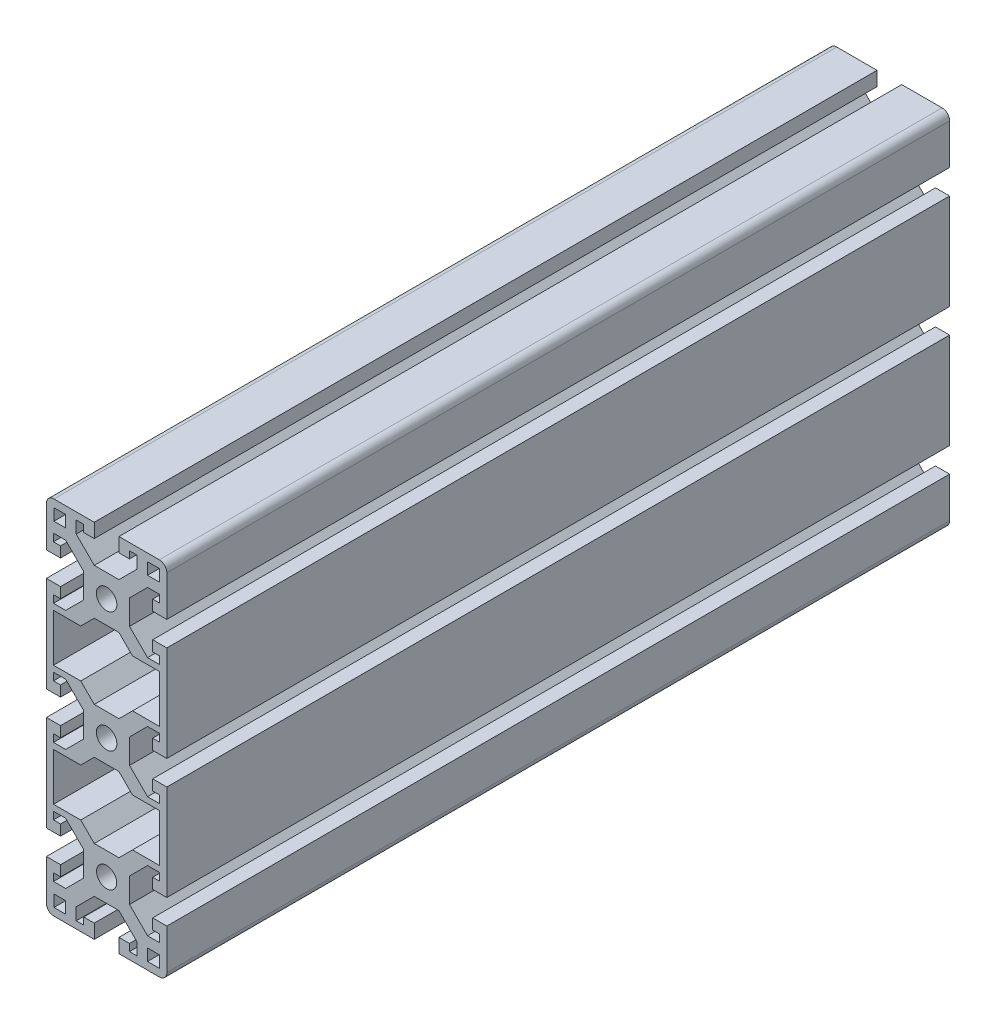
SolidWorks part; units mm, degrees
material "6063-T6"
ref_plane "Front Plane" through (0, 0, 0) normal (0, 0, 1) x (1, 0, 0)
ref_plane "Top Plane" through (0, 0, 0) normal (0, 1, 0) x (1, 0, 0)
ref_plane "Right Plane" through (0, 0, 0) normal (1, 0, 0) x (0, 0, -1)
sketch "Sketch1" plane through (0, 0, 0) normal (0, 1, 0) x (1, 0, 0)
  line L0 (0, -130) -> (0, 130)
  dimension "D1" = 260
other "40 series TS40-120LM(1)"
ref_plane "Plane1" through (0, 0, 130) normal (0, 0, -1) x (-1, 0, 0)
sketch "Sketch22" plane through (0, 0, 130) normal (0, 0, -1) x (-1, 0, 0)
  line L0 (15.3, -35.9) -> (20, -35.9)
  line L1 (3.35, 0) -> (7.6, 0) construction
  line L2 (7.6, 4.1) -> (7.6, -4.1)
  line L3 (7.6, -4.1) -> (13.6, -10.1)
  line L4 (13.6, -10.1) -> (17.65, -10.1)
  line L5 (17.65, -10.1) -> (17.65, -7.6)
  line L6 (17.65, -7.6) -> (15.3, -7.6)
  line L7 (15.3, -7.6) -> (15.3, -4.1)
  line L8 (15.3, -4.1) -> (20, -4.1)
  line L9 (20, -4.1) -> (20, -35.9)
  line L10 (0, -3.35) -> (0, -7.6) construction
  line L11 (-4.1, -7.6) -> (4.1, -7.6)
  line L12 (4.1, -7.6) -> (8.6, -12.1)
  line L13 (8.6, -12.1) -> (17.65, -12.1)
  line L14 (17.65, -12.1) -> (17.65, -27.9)
  line L15 (20, -20) -> (0, 0) construction
  line L16 (17.65, -20) -> (20, -20) construction
  line L17 (15.3, -32.4) -> (15.3, -35.9)
  line L18 (17.65, -32.4) -> (15.3, -32.4)
  line L19 (17.65, -29.9) -> (17.65, -32.4)
  line L20 (13.6, -29.9) -> (17.65, -29.9)
  line L21 (8.6, -27.9) -> (17.65, -27.9)
  line L22 (7.6, -35.9) -> (13.6, -29.9)
  line L23 (7.6, -44.1) -> (7.6, -35.9)
  line L24 (4.1, -32.4) -> (8.6, -27.9)
  line L25 (-4.1, -32.4) -> (4.1, -32.4)
  line L26 (3.35, -40) -> (7.6, -40) construction
  line L27 (15.3, -44.1) -> (20, -44.1)
  line L28 (15.3, -47.6) -> (15.3, -44.1)
  line L29 (17.65, -47.6) -> (15.3, -47.6)
  line L30 (17.65, -50.1) -> (17.65, -47.6)
  line L31 (13.6, -50.1) -> (17.65, -50.1)
  line L32 (7.6, -44.1) -> (13.6, -50.1)
  line L33 (0, -40) -> (19.2678, -59.2678) construction
  line L34 (20, -57.5) -> (20, -44.1)
  line L35 (17.5, -60) -> (4.1, -60)
  line L36 (4.1, -55.3) -> (4.1, -60)
  line L37 (7.6, -55.3) -> (4.1, -55.3)
  line L38 (7.6, -57.65) -> (7.6, -55.3)
  line L39 (10.1, -57.65) -> (7.6, -57.65)
  line L40 (10.1, -53.6) -> (10.1, -57.65)
  line L41 (4.1, -47.6) -> (10.1, -53.6)
  line L42 (4.1, -47.6) -> (-4.1, -47.6)
  line L43 (0, -40) -> (-19.2678, -59.2678) construction
  line L44 (-3.35, -40) -> (-7.6, -40) construction
  line L45 (-17.65, -20) -> (-20, -20) construction
  line L46 (-20, -20) -> (0, 0) construction
  line L47 (-3.35, 0) -> (-7.6, 0) construction
  line L48 (-4.1, -47.6) -> (-10.1, -53.6)
  line L49 (-10.1, -53.6) -> (-10.1, -57.65)
  line L50 (-10.1, -57.65) -> (-7.6, -57.65)
  line L51 (-7.6, -57.65) -> (-7.6, -55.3)
  line L52 (-7.6, -55.3) -> (-4.1, -55.3)
  line L53 (-4.1, -55.3) -> (-4.1, -60)
  line L54 (-17.5, -60) -> (-4.1, -60)
  line L55 (-20, -57.5) -> (-20, -44.1)
  line L56 (-7.6, -44.1) -> (-13.6, -50.1)
  line L57 (-13.6, -50.1) -> (-17.65, -50.1)
  line L58 (-17.65, -50.1) -> (-17.65, -47.6)
  line L59 (-17.65, -47.6) -> (-15.3, -47.6)
  line L60 (-15.3, -47.6) -> (-15.3, -44.1)
  line L61 (-15.3, -44.1) -> (-20, -44.1)
  line L62 (-4.1, -32.4) -> (-8.6, -27.9)
  line L63 (-7.6, -44.1) -> (-7.6, -35.9)
  line L64 (-7.6, -35.9) -> (-13.6, -29.9)
  line L65 (-8.6, -27.9) -> (-17.65, -27.9)
  line L66 (-13.6, -29.9) -> (-17.65, -29.9)
  line L67 (-17.65, -29.9) -> (-17.65, -32.4)
  line L68 (-17.65, -32.4) -> (-15.3, -32.4)
  line L69 (-15.3, -32.4) -> (-15.3, -35.9)
  line L70 (-17.65, -12.1) -> (-17.65, -27.9)
  line L71 (-8.6, -12.1) -> (-17.65, -12.1)
  line L72 (-4.1, -7.6) -> (-8.6, -12.1)
  line L73 (-20, -4.1) -> (-20, -35.9)
  line L74 (-15.3, -4.1) -> (-20, -4.1)
  line L75 (-15.3, -7.6) -> (-15.3, -4.1)
  line L76 (-17.65, -7.6) -> (-15.3, -7.6)
  line L77 (-17.65, -10.1) -> (-17.65, -7.6)
  line L78 (-13.6, -10.1) -> (-17.65, -10.1)
  line L79 (-7.6, -4.1) -> (-13.6, -10.1)
  line L80 (-7.6, 4.1) -> (-7.6, -4.1)
  line L81 (-15.3, -35.9) -> (-20, -35.9)
  line L82 (-20, 20) -> (0, 0) construction
  line L83 (-17.65, 20) -> (-20, 20) construction
  line L84 (-3.35, 40) -> (-7.6, 40) construction
  line L85 (0, 40) -> (-19.2678, 59.2678) construction
  line L86 (0, 40) -> (19.2678, 59.2678) construction
  line L87 (3.35, 40) -> (7.6, 40) construction
  line L88 (17.65, 20) -> (20, 20) construction
  line L89 (20, 20) -> (0, 0) construction
  line L90 (0, 3.35) -> (0, 7.6) construction
  line L91 (-15.3, 35.9) -> (-20, 35.9)
  line L92 (-7.6, 4.1) -> (-13.6, 10.1)
  line L93 (-13.6, 10.1) -> (-17.65, 10.1)
  line L94 (-17.65, 10.1) -> (-17.65, 7.6)
  line L95 (-17.65, 7.6) -> (-15.3, 7.6)
  line L96 (-15.3, 7.6) -> (-15.3, 4.1)
  line L97 (-15.3, 4.1) -> (-20, 4.1)
  line L98 (-20, 4.1) -> (-20, 35.9)
  line L99 (-4.1, 7.6) -> (-8.6, 12.1)
  line L100 (-8.6, 12.1) -> (-17.65, 12.1)
  line L101 (-17.65, 12.1) -> (-17.65, 27.9)
  line L102 (-15.3, 32.4) -> (-15.3, 35.9)
  line L103 (-17.65, 32.4) -> (-15.3, 32.4)
  line L104 (-17.65, 29.9) -> (-17.65, 32.4)
  line L105 (-13.6, 29.9) -> (-17.65, 29.9)
  line L106 (-8.6, 27.9) -> (-17.65, 27.9)
  line L107 (-7.6, 35.9) -> (-13.6, 29.9)
  line L108 (-7.6, 44.1) -> (-7.6, 35.9)
  line L109 (-4.1, 32.4) -> (-8.6, 27.9)
  line L110 (-15.3, 44.1) -> (-20, 44.1)
  line L111 (-15.3, 47.6) -> (-15.3, 44.1)
  line L112 (-17.65, 47.6) -> (-15.3, 47.6)
  line L113 (-17.65, 50.1) -> (-17.65, 47.6)
  line L114 (-13.6, 50.1) -> (-17.65, 50.1)
  line L115 (-7.6, 44.1) -> (-13.6, 50.1)
  line L116 (-20, 57.5) -> (-20, 44.1)
  line L117 (-17.5, 60) -> (-4.1, 60)
  line L118 (-4.1, 55.3) -> (-4.1, 60)
  line L119 (-7.6, 55.3) -> (-4.1, 55.3)
  line L120 (-7.6, 57.65) -> (-7.6, 55.3)
  line L121 (-10.1, 57.65) -> (-7.6, 57.65)
  line L122 (-10.1, 53.6) -> (-10.1, 57.65)
  line L123 (-4.1, 47.6) -> (-10.1, 53.6)
  line L124 (4.1, 47.6) -> (-4.1, 47.6)
  line L125 (4.1, 47.6) -> (10.1, 53.6)
  line L126 (10.1, 53.6) -> (10.1, 57.65)
  line L127 (10.1, 57.65) -> (7.6, 57.65)
  line L128 (7.6, 57.65) -> (7.6, 55.3)
  line L129 (7.6, 55.3) -> (4.1, 55.3)
  line L130 (4.1, 55.3) -> (4.1, 60)
  line L131 (17.5, 60) -> (4.1, 60)
  line L132 (20, 57.5) -> (20, 44.1)
  line L133 (7.6, 44.1) -> (13.6, 50.1)
  line L134 (13.6, 50.1) -> (17.65, 50.1)
  line L135 (17.65, 50.1) -> (17.65, 47.6)
  line L136 (17.65, 47.6) -> (15.3, 47.6)
  line L137 (15.3, 47.6) -> (15.3, 44.1)
  line L138 (15.3, 44.1) -> (20, 44.1)
  line L139 (-4.1, 32.4) -> (4.1, 32.4)
  line L140 (4.1, 32.4) -> (8.6, 27.9)
  line L141 (7.6, 44.1) -> (7.6, 35.9)
  line L142 (7.6, 35.9) -> (13.6, 29.9)
  line L143 (8.6, 27.9) -> (17.65, 27.9)
  line L144 (13.6, 29.9) -> (17.65, 29.9)
  line L145 (17.65, 29.9) -> (17.65, 32.4)
  line L146 (17.65, 32.4) -> (15.3, 32.4)
  line L147 (15.3, 32.4) -> (15.3, 35.9)
  line L148 (17.65, 12.1) -> (17.65, 27.9)
  line L149 (8.6, 12.1) -> (17.65, 12.1)
  line L150 (4.1, 7.6) -> (8.6, 12.1)
  line L151 (-4.1, 7.6) -> (4.1, 7.6)
  line L152 (20, 4.1) -> (20, 35.9)
  line L153 (15.3, 4.1) -> (20, 4.1)
  line L154 (15.3, 7.6) -> (15.3, 4.1)
  line L155 (17.65, 7.6) -> (15.3, 7.6)
  line L156 (17.65, 10.1) -> (17.65, 7.6)
  line L157 (13.6, 10.1) -> (17.65, 10.1)
  line L158 (7.6, 4.1) -> (13.6, 10.1)
  line L159 (15.3, 35.9) -> (20, 35.9)
  line L161 (13.6, -53.6) -> (17.5, -53.6)
  line L162 (13.6, -53.6) -> (13.6, -57.5)
  line L163 (13.6, -57.5) -> (17.5, -57.5)
  line L164 (17.5, -53.6) -> (17.5, -57.5)
  line L165 (-17.5, -57.5) -> (-13.6, -57.5)
  line L166 (-17.5, -57.5) -> (-17.5, -53.6)
  line L167 (-17.5, -53.6) -> (-13.6, -53.6)
  line L168 (-13.6, -57.5) -> (-13.6, -53.6)
  line L169 (-17.5, 57.5) -> (-13.6, 57.5)
  line L170 (-17.5, 57.5) -> (-17.5, 53.6)
  line L171 (-17.5, 53.6) -> (-13.6, 53.6)
  line L172 (-13.6, 57.5) -> (-13.6, 53.6)
  line L173 (17.5, 57.5) -> (13.6, 57.5)
  line L174 (17.5, 57.5) -> (17.5, 53.6)
  line L175 (17.5, 53.6) -> (13.6, 53.6)
  line L176 (13.6, 57.5) -> (13.6, 53.6)
  arc A0 (0, -43.35) -> (0, -36.65) centre (0, -40) ccw
  arc A1 (3.35, 0) -> (-3.35, 0) centre (0, 0) cw
  arc A2 (17.5, -60) -> (20, -57.5) centre (17.5, -57.5) ccw
  arc A3 (-17.5, -60) -> (-20, -57.5) centre (-17.5, -57.5) cw
  arc A4 (0, -43.35) -> (0, -36.65) centre (0, -40) cw
  arc A5 (0, 43.35) -> (0, 36.65) centre (0, 40) ccw
  arc A6 (-17.5, 60) -> (-20, 57.5) centre (-17.5, 57.5) ccw
  arc A7 (17.5, 60) -> (20, 57.5) centre (17.5, 57.5) cw
  arc A8 (3.35, 0) -> (-3.35, 0) centre (0, 0) ccw
  arc A9 (0, 43.35) -> (0, 36.65) centre (0, 40) cw
  point P19 (17.65, -4.1)
  point P65 (0, -47.6)
  point P79 (0, -32.4)
  point P196 (0, 32.4)
  point P197 (0, 47.6)
  point P201 (20, -60)
  point P202 (-20, -60)
  point P203 (20, -40)
  point P204 (-20, -40)
  point P205 (20, -20)
  point P206 (0, -60)
  point P207 (0, -40)
  point P208 (-20, -20)
  point P209 (-20, 0)
  point P210 (20, 0)
  point P211 (20, 40)
  point P212 (0, 0)
  point P213 (-20, 20)
  point P214 (20, 20)
  point P215 (-20, 40)
  point P216 (0, 40)
  point P217 (20, 60)
  point P218 (0, 60)
  point P219 (-20, 60)
  point P220 (0, 20)
  point P221 (0, -20)
  point P222 (0, 0)
  dimension "D2" = 4.1
  dimension "D4" = 12.4
  dimension "D9" = 2.5
  dimension "D3" = 3.35
  dimension "D5" = 20
  dimension "D10" = 20
  dimension "D6" = 10.1
  dimension "D8" = 2
  dimension "D11" = 2.5
  dimension "D7" = 4.7
hole_wizard "M8x1.25 Tapped Hole1" positions "Sketch3" profile "Sketch4" tap size "M8x1.25" standard "ANSI Metric"
sketch "Sketch3" plane through (0, 0, 130) normal (0, 0, 1) x (1, 0, 0)
  point P0 (0, 0)
  point P3 (0, 40)
sketch "Sketch4" plane through (0, 0, 130) normal (1, 0, 0) x (0, -1, 0)
  line L0 (0, 0) -> (0, 32.0429)
  line L1 (0, 32.0429) -> (3.4, 30)
  line L2 (3.4, 30) -> (3.4, 0)
  line L5 (3.4, 0) -> (0, 0)
  line L10 (0, 32.0429) -> (-3.4, 30) construction
  line L11 (0, -6.35) -> (0, 107.95) construction
  dimension "Tap Drill Dia." = 6.8
  dimension "Tap Drill Depth" = 30
  dimension "Drill Angle" = 118
cosmetic thread "Hole Thread1" parameters "D1"=25, "D2"=8
cosmetic thread "Hole Thread2" parameters "D1"=25, "D2"=8
mirror "Mirror1" about plane through (0, 0, 0) normal (0, 0, 1) of "M8x1.25 Tapped Hole1"
cosmetic thread "Hole Thread3" parameters "D1"=25, "D2"=8
cosmetic thread "Hole Thread4" parameters "D1"=25, "D2"=8
